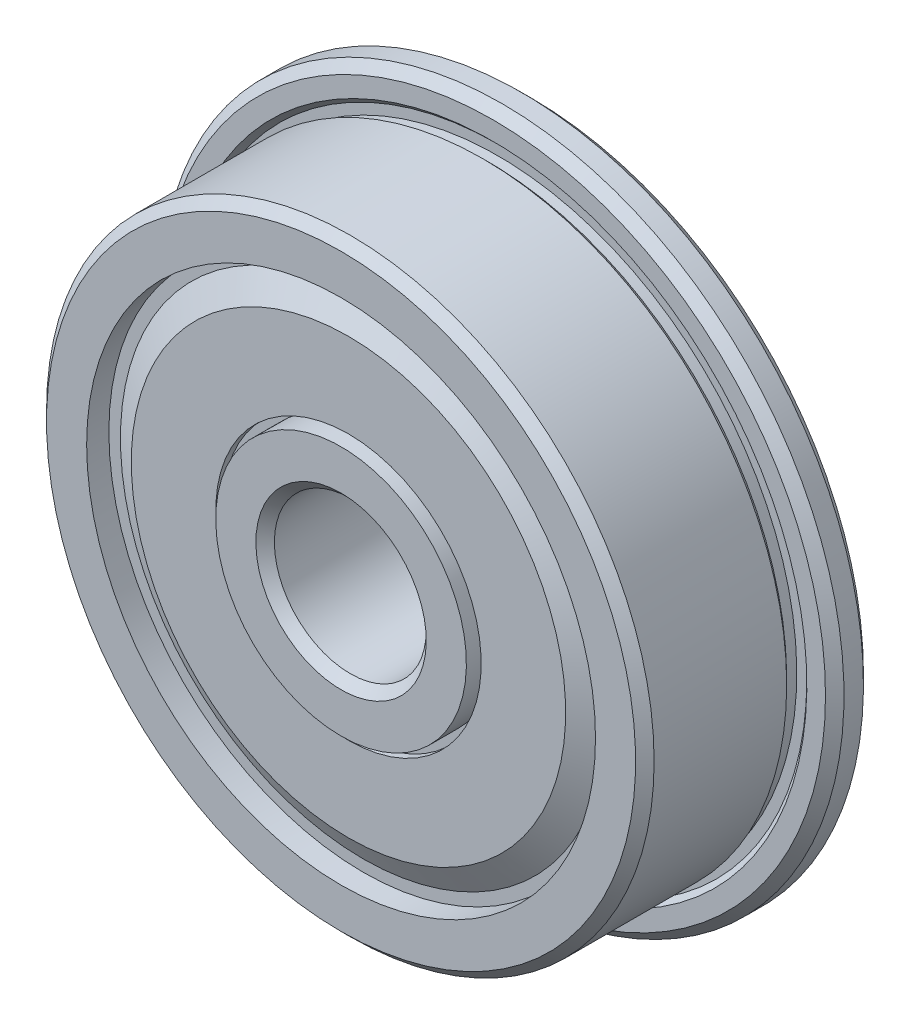
SolidWorks part; units mm, degrees
ref_plane "Front Plane" through (0, 0, 0) normal (0, 0, 1) x (1, 0, 0)
ref_plane "Top Plane" through (0, 0, 0) normal (0, 1, 0) x (1, 0, 0)
ref_plane "Right Plane" through (0, 0, 0) normal (1, 0, 0) x (0, 0, -1)
sketch "Sketch1" plane through (0, 0, 0) normal (1, 0, 0) x (0, 0, -1)
  line L0 (0, 8) -> (0, -8) construction
  line L1 (-2.5, 8) -> (2.5, 8) construction
  line L2 (0, 0) -> (2.5, 0) construction
  line L3 (2.5, 9) -> (2.5, -9) construction
  line L4 (2.5, -9) -> (1.5, -9) construction
  line L5 (2.5, 2) -> (0, 2) construction
  line L6 (2.5, 2) -> (2.5, -2) construction
  dimension "OD" = 16
  dimension "Width" = 5
  dimension "Flange Thickness" = 1
  dimension "ID" = 4
  dimension "Flange OD" = 18
sketch "Sketch2" plane through (0, 0, 0) normal (1, 0, 0) x (0, 0, -1)
  line L0 (2.5, 9) -> (1.5, 9)
  line L1 (1.5, 9) -> (1.5, 8.2652)
  line L2 (1.2348, 8) -> (-2.5, 8)
  line L3 (-2.5, 8) -> (-2.5, 6.05)
  line L4 (-2.5, 6.05) -> (-0.5611, 6.05)
  line L5 (2.5, 9) -> (2.5, -9) construction
  line L6 (2.5, 6.05) -> (2.5, 9)
  line L7 (2.5, 2) -> (-2.5, 2)
  line L8 (-2.5, 2) -> (-2.5, 3.95)
  line L9 (-2.5, 3.95) -> (-0.5611, 3.95)
  line L10 (2.5, 3.95) -> (2.5, 2)
  line L11 (0, 8) -> (0, 2) construction
  line L12 (-1.1905, 5) -> (1.1905, 5) construction
  line L13 (0.5611, 6.05) -> (2.5, 6.05)
  line L14 (0.5611, 3.95) -> (2.5, 3.95)
  line L15 (1.5, 8.2652) -> (1.6326, 8.1326)
  line L16 (1.6326, 8.1326) -> (1.6326, 7.8674)
  line L17 (1.6326, 7.8674) -> (1.3674, 7.8674)
  line L18 (1.3674, 7.8674) -> (1.2348, 8)
  line L19 (1.5, 8) -> (1.6326, 7.8674) construction
  line L20 (1.6326, 8.1326) -> (1.3674, 7.8674) construction
  line L21 (1.2348, 8) -> (1.5, 8) construction
  line L22 (1.5, 8) -> (1.5, 8.2652) construction
  line L23 (-2.5, 0) -> (2.5, 0) construction
  circle A0 centre (0, 5) radius 1.1905 construction
  arc A1 (-0.5611, 6.05) -> (0.5611, 6.05) centre (0, 5) cw
  arc A2 (-0.5611, 3.95) -> (0.5611, 3.95) centre (0, 5) ccw
  dimension "Ball Dia." = 2.381
  dimension "D2" = 135
  dimension "D3" = 0.375
  dimension "Race Thikness" = 1.95
  dimension "D4" = 2.1
revolve "Revolve1" add sketch "Sketch2" angle 360 about L2
fillet "Fillet1" radius 0.2438 3 edges at (0, -9, -2.5) (0, -9, -1.5) (0, -8, 2.5) profile chamfer
sketch "Sketch3" plane through (0, 0, 0) normal (0, 0, 1) x (1, 0, 0)
  line L0 (-2, 0) -> (2, 0) construction
  line L1 (-8, 0) -> (8, 0) construction
  point P5 (0, 0)
  dimension "ID2" = 4
  dimension "OD2" = 16
fillet "Fillet2" radius 0.2438 2 edges at (0, -2, -2.5) (0, -2, 2.5) profile chamfer
sketch "Sketch7" plane through (0, 0, 0) normal (0, 0, 1) x (1, 0, 0)
  line L0 (0, 6.1905) -> (0, 3.8095)
  line L1 (0, 9) -> (0, -9) construction
  line L2 (-1.5176, 6.1905) -> (0, 0) construction
  line L3 (0, 0) -> (1.5176, 6.1905) construction
  line L4 (1.5176, 6.1905) -> (-1.5176, 6.1905) construction
  circle A0 centre (0, 5) radius 1.1905 construction
  circle A1 centre (0, 0) radius 6.1905 construction
  circle A2 centre (0, 0) radius 3.8095 construction
  arc A4 (0, 6.1905) -> (0, 3.8095) centre (0, 5) ccw
  dimension "D1" = 27.549
revolve "Revolve3" add sketch "Sketch7" angle 360 about L0
pattern_circular "CirPattern3" count 9 over 360 about axis through (0, 0, 0) along (0, 0, 1) of bodies 107
sketch "Sketch8" plane through (0, 0, 0) normal (1, 0, 0) x (0, 0, -1)
  line L1 (-2.5, 6.05) -> (-1.72, 6.05)
  line L2 (-2.5, 6.05) -> (-2.5, 6.7)
  line L3 (-2.5, 6.7) -> (-1.72, 6.7)
  line L4 (-1.72, 6.05) -> (-1.72, 6.7)
  line L5 (2.5, 6.05) -> (1.72, 6.05)
  line L6 (2.5, 6.05) -> (2.5, 6.7)
  line L7 (2.5, 6.7) -> (1.72, 6.7)
  line L8 (1.72, 6.05) -> (1.72, 6.7)
  line L9 (2.5, 3.95) -> (1.72, 3.95)
  line L10 (2.5, 3.95) -> (2.5, 3.3)
  line L11 (2.5, 3.3) -> (1.72, 3.3)
  line L12 (1.72, 3.95) -> (1.72, 3.3)
  line L13 (-2.5, 3.95) -> (-1.72, 3.95)
  line L14 (-2.5, 3.95) -> (-2.5, 3.3)
  line L15 (-2.5, 3.3) -> (-1.72, 3.3)
  line L16 (-1.72, 3.95) -> (-1.72, 3.3)
  dimension "D1" = 0.65
  dimension "D2" = 0.78
revolve "Cut-Revolve1" cut sketch "Sketch8" angle 360 about L2
sketch "Sketch9" plane through (0, 0, 0) normal (1, 0, 0) x (0, 0, -1)
  line L0 (-1.72, 6.7) -> (-1.72, 6.3429)
  line L1 (-1.72, 6.3429) -> (-2.11, 5.6674)
  line L2 (-2.11, 5.6674) -> (-2.11, 3.495)
  line L3 (2.11, 3.495) -> (2.11, 3.3) construction
  line L4 (1.72, 6.7) -> (1.72, 6.3429)
  line L5 (1.72, 6.3429) -> (2.11, 5.6674)
  line L6 (2.11, 5.6674) -> (2.11, 3.495)
  line L7 (2.5, 3.3) -> (1.72, 3.3) construction
  line L8 (-1.915, 6.7) -> (-1.915, 6.3951)
  line L9 (-1.915, 6.3951) -> (-2.305, 5.7196)
  line L10 (-2.305, 5.7196) -> (-2.305, 3.495)
  line L11 (-1.72, 6.7) -> (-1.915, 6.7)
  line L12 (-2.11, 3.495) -> (-2.305, 3.495)
  line L13 (1.915, 6.7) -> (1.915, 6.3951)
  line L14 (1.915, 6.3951) -> (2.305, 5.7196)
  line L15 (2.305, 5.7196) -> (2.305, 3.495)
  line L16 (1.72, 6.7) -> (1.915, 6.7)
  line L17 (2.11, 3.495) -> (2.305, 3.495)
  line L18 (-1.72, 6.3429) -> (-1.72, 2.5308) construction
  line L19 (1.72, 6.3429) -> (1.72, 6.7) construction
  line L20 (-1.72, 3.3) -> (-2.5, 3.3) construction
  line L22 (-2.11, 3.495) -> (-2.11, 3.3) construction
  dimension "D2" = 150
  dimension "D1" = 150
  dimension "D5" = 0.78
  dimension "D3" = 0.195
  dimension "D4" = 0.195
  dimension "D6" = 0.3571
revolve "Revolve4" add sketch "Sketch9" angle 360 about L2
equation "\"D1@Fillet1\"=\"Race Thikness@Sketch2\"/8"
equation "\"ID2@Sketch3\" = \"ID@Sketch1\""
equation "\"OD2@Sketch3\" = \"OD@Sketch1\""
equation "\"D1@Fillet2\"=\"Race Thikness@Sketch2\"/8"
equation "\"D1@CirPattern3\"=360/\"D1@Sketch7\"-4"
equation "\"D1@Sketch8\"=\"Race Thikness@Sketch2\"/3"
equation "\"D2@Sketch8\"=\"Race Thikness@Sketch2\"/2.5"
equation "\"D3@Sketch9\"=\"D5@Sketch9\"/4"
equation "\"D4@Sketch9\"=\"D5@Sketch9\"/4"
equation "\"D1@Sketch9\"=\"D2@Sketch9\""
equation "\"Ball Dia.@Sketch2\" = \"D1@Sketch2\"*.5"
equation "\"D4@Sketch2\"=((\"OD@Sketch1\"-\"ID@Sketch1\")/2)*.35"
